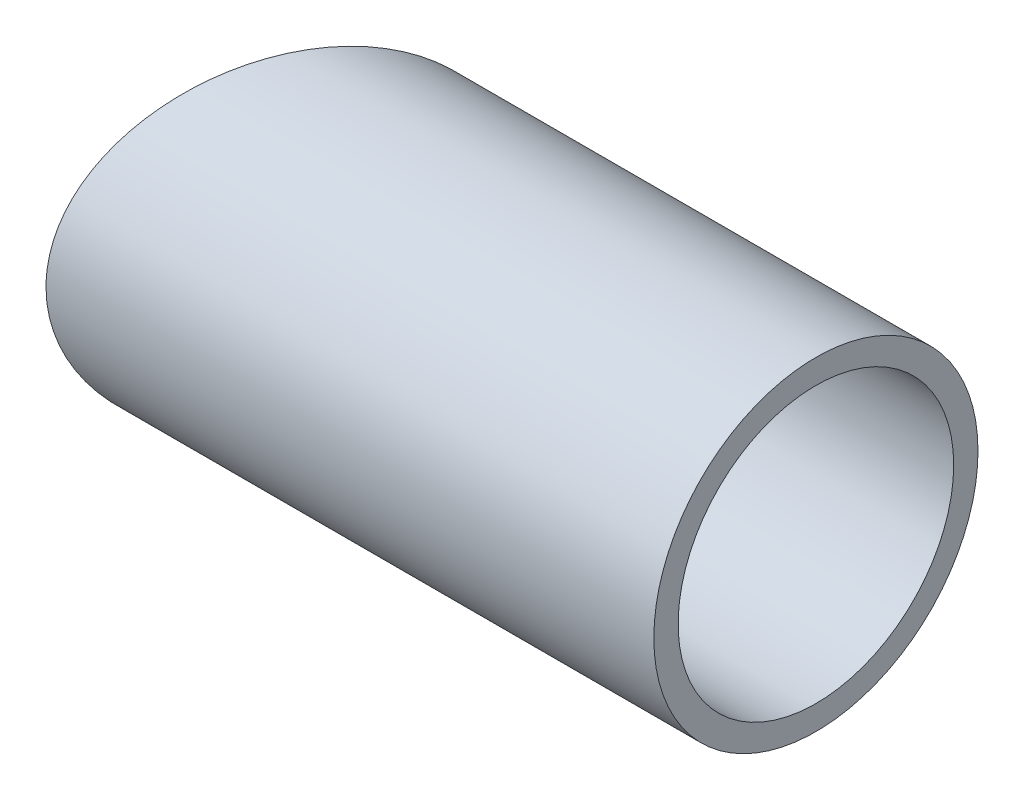
SolidWorks part; units mm, degrees
material "Galvanized Steel"
ref_plane "Front Plane" through (0, 0, 0) normal (0, 0, 1) x (1, 0, 0)
ref_plane "Top Plane" through (0, 0, 0) normal (0, 1, 0) x (1, 0, 0)
ref_plane "Right Plane" through (0, 0, 0) normal (1, 0, 0) x (0, 0, -1)
sketch "Sketch1" plane through (0, 0, 0) normal (1, 0, 0) x (0, 0, -1)
  circle A0 centre (0, 0) radius 20
  dimension "D1" = 40
extrude "Boss-Extrude1" add sketch "Sketch1" along normal blind 75
sketch "Sketch3" plane through (75, 0, 0) normal (1, 0, 0) x (0, 0, -1)
  circle A0 centre (0, 0) radius 14.5
  dimension "D1" = 29
extrude "Cut-Extrude2" cut sketch "Sketch3" against normal through all both and the other way through all
sketch "Sketch4" plane through (75, 0, 0) normal (1, 0, 0) x (0, 0, -1)
  circle A0 centre (0, 0) radius 17
  dimension "D1" = 34
extrude "Cut-Extrude3" cut sketch "Sketch4" against normal blind 25
ref_plane "Plane1" through (0, 20, 0) normal (0, 1, 0) x (1, 0, 0)
sketch "Sketch5" plane through (0, 0, 0) normal (0, 1, 0) x (1, 0, 0)
  circle A0 centre (-376.6992, 180) radius 426.5
  dimension "D1" = 853
  dimension "D2" = 180
extrude "Cut-Extrude4" cut sketch "Sketch5" against normal through all both and the other way through all
